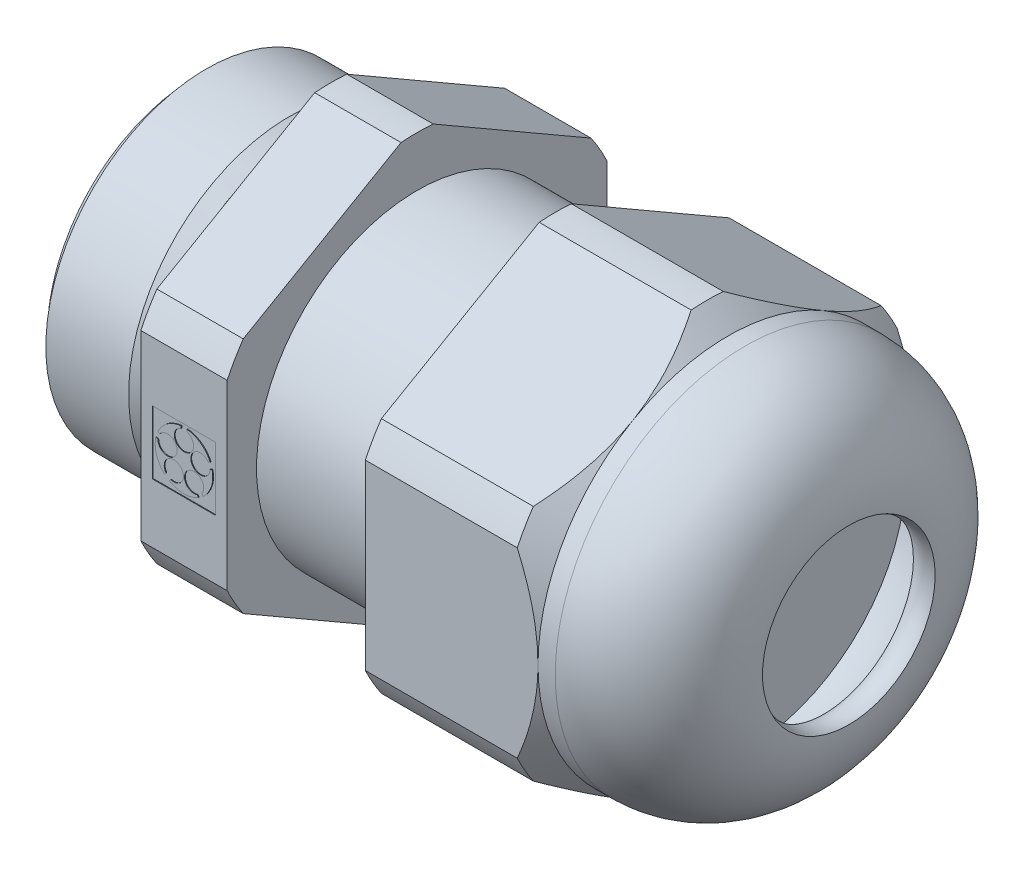
SolidWorks part; units mm, degrees
ref_plane "Face" through (0, 0, 0) normal (0, 0, 1) x (1, 0, 0)
ref_plane "Dessus" through (0, 0, 0) normal (0, 1, 0) x (1, 0, 0)
ref_plane "Droite" through (0, 0, 0) normal (1, 0, 0) x (0, 0, -1)
ref_plane "Plan1" through (0, 0, 0) normal (0, 0, 1) x (1, 0, 0)
sketch "Esquisse1" plane through (0, 0, 0) normal (0, 0, 1) x (1, 0, 0)
  line L0 (0, 8.105) -> (0, 2.73)
  line L1 (0.73, 2) -> (32, 2)
  line L2 (32, 2) -> (32, 9.3)
  line L3 (32, 11) -> (31, 11)
  line L4 (31, 11) -> (27.3333, 14.6667)
  line L5 (27.3333, 14.6667) -> (21, 14.6667)
  line L6 (21, 14.6667) -> (21, 9.3)
  line L7 (21, 9.3) -> (13, 9.3)
  line L8 (13, 9.3) -> (13, 14.6667)
  line L9 (13, 14.6667) -> (8, 14.6667)
  line L10 (8, 14.6667) -> (8, 8.835)
  line L11 (8, 8.835) -> (6.4, 8.835)
  line L12 (6.4, 8.835) -> (5.5946, 9.3)
  line L13 (5.5946, 9.3) -> (0.8, 9.3)
  line L14 (0.8, 9.3) -> (0.8, 8.835)
  line L15 (0.8, 8.835) -> (0.73, 8.835)
  line L16 (38, 0) -> (0, 0) construction
  arc A0 (0, 2.73) -> (0.73, 2) centre (0.73, 2.73) ccw
  arc A1 (32, 9.3) -> (36.2306, 5.7694) centre (32, 5) cw
  arc A2 (36.2306, 5.7694) -> (38, 5) centre (37.3999, 6.0392) ccw
  arc A3 (38, 5) -> (32, 11) centre (32, 5) ccw
  arc A4 (0.73, 8.835) -> (0, 8.105) centre (0.73, 8.105) ccw
revolve "Révolution1" add sketch "Esquisse1" angle 360 about L16
cosmetic thread "Représentation de filetage1" parameters "D1"=7.535, "D2"=17.67
cosmetic thread "Représentation de filetage2" parameters "D1"=5.6, "D2"=17.67
ref_plane "Plan2" through (8, 0, 0) normal (1, 0, 0) x (0, 0, -1)
sketch "Esquisse2" plane through (8, 0, 0) normal (1, 0, 0) x (0, 0, -1)
  line L0 (-22, -22) -> (22, -22)
  line L1 (22, -22) -> (22, 22)
  line L2 (22, 22) -> (-22, 22)
  line L3 (-22, 22) -> (-22, -22)
  line L4 (-11, 5.2764) -> (-11, -5.2764)
  line L5 (-10.0695, -6.8881) -> (-0.9305, -12.1645)
  line L6 (0.9305, -12.1645) -> (10.0695, -6.8881)
  line L7 (11, -5.2764) -> (11, 5.2764)
  line L8 (10.0695, 6.8881) -> (0.9305, 12.1645)
  line L9 (-0.9305, 12.1645) -> (-10.0695, 6.8881)
  arc A0 (-11, -5.2764) -> (-10.0695, -6.8881) centre (0, 0) ccw
  arc A1 (-0.9305, -12.1645) -> (0.9305, -12.1645) centre (0, 0) ccw
  arc A2 (10.0695, -6.8881) -> (11, -5.2764) centre (0, 0) ccw
  arc A3 (11, 5.2764) -> (10.0695, 6.8881) centre (0, 0) ccw
  arc A4 (0.9305, 12.1645) -> (-0.9305, 12.1645) centre (0, 0) ccw
  arc A5 (-10.0695, 6.8881) -> (-11, 5.2764) centre (0, 0) ccw
extrude "Enlèv. mat.-Extru.1" cut sketch "Esquisse2" along normal blind 38
ref_plane "Plan3" through (0, 0, 11) normal (0, 0, 1) x (1, 0, 0)
sketch "Esquisse3" plane through (0, 0, 11) normal (0, 0, 1) x (1, 0, 0)
  line L0 (8.6667, -1.8333) -> (12.3333, -1.8333)
  line L1 (12.3333, -1.8333) -> (12.3333, 1.8333)
  line L2 (12.3333, 1.8333) -> (8.6667, 1.8333)
  line L3 (8.6667, 1.8333) -> (8.6667, -1.8333)
  line L4 (9.3904, -1.2436) -> (9.4659, -1.1398)
  line L5 (9.7355, -1.3357) -> (9.6601, -1.4396)
  line L6 (11.3399, -1.4396) -> (11.2645, -1.3357)
  line L7 (11.5341, -1.1398) -> (11.6096, -1.2436)
  line L8 (12.1287, 0.3539) -> (12.0066, 0.3143)
  line L9 (11.9036, 0.6313) -> (12.0256, 0.671)
  line L10 (10.6667, 1.6583) -> (10.6667, 1.53)
  line L11 (10.3333, 1.53) -> (10.3333, 1.6583)
  line L12 (8.9744, 0.671) -> (9.0964, 0.6313)
  line L13 (8.9934, 0.3143) -> (8.8713, 0.3539)
  arc A0 (8.8713, 0.3539) -> (9.3904, -1.2436) centre (10.5, 0) ccw
  arc A1 (9.4659, -1.1398) -> (9.7355, -1.3357) centre (9.9122, -0.809) cw
  arc A2 (9.6601, -1.4396) -> (11.3399, -1.4396) centre (10.5, 0) ccw
  arc A3 (11.2645, -1.3357) -> (11.5341, -1.1398) centre (11.0878, -0.809) cw
  arc A4 (11.6096, -1.2436) -> (12.1287, 0.3539) centre (10.5, 0) ccw
  arc A5 (12.0066, 0.3143) -> (11.9036, 0.6313) centre (11.4511, 0.309) cw
  arc A6 (12.0256, 0.671) -> (10.6667, 1.6583) centre (10.5, 0) ccw
  arc A7 (10.6667, 1.53) -> (10.3333, 1.53) centre (10.5, 1) cw
  arc A8 (10.3333, 1.6583) -> (8.9744, 0.671) centre (10.5, 0) ccw
  arc A9 (9.0964, 0.6313) -> (8.9934, 0.3143) centre (9.5489, 0.309) cw
extrude "Enlèv. mat.-Extru.2" cut sketch "Esquisse3" against normal blind 0.044
